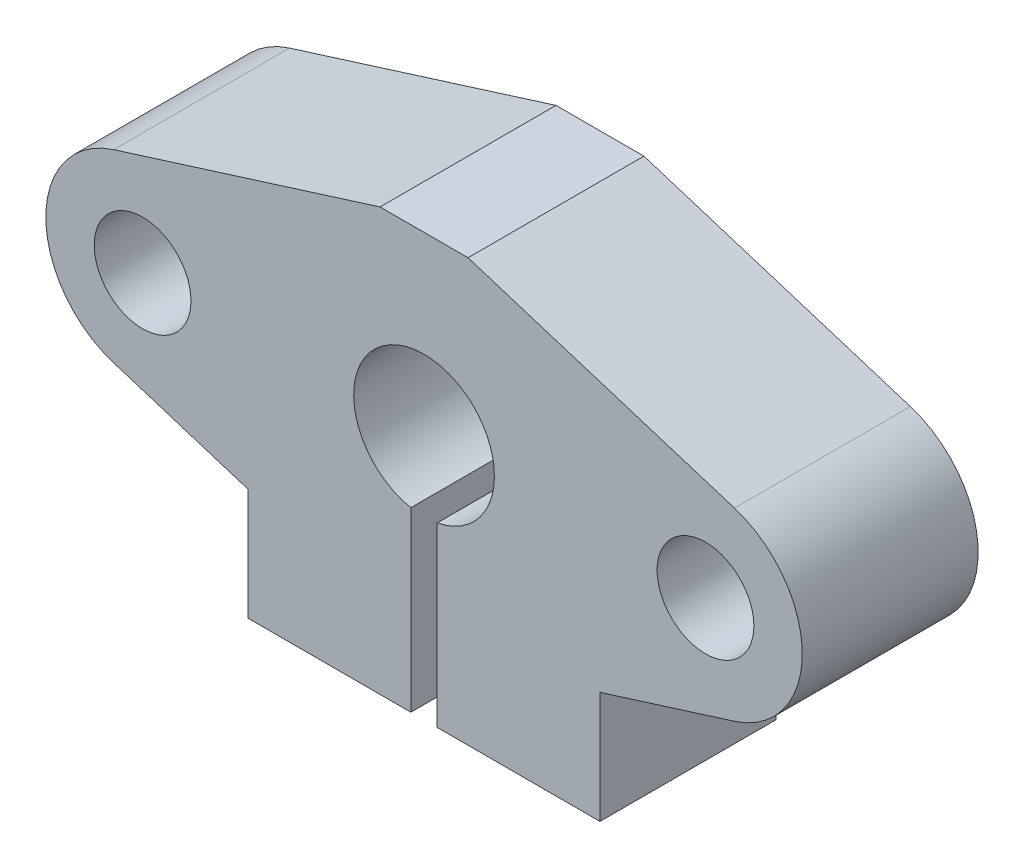
SolidWorks part; units mm, degrees
ref_plane "前视基准面" through (0, 0, 0) normal (0, 0, 1) x (1, 0, 0)
ref_plane "上视基准面" through (0, 0, 0) normal (0, 1, 0) x (1, 0, 0)
ref_plane "右视基准面" through (0, 0, 0) normal (1, 0, 0) x (0, 0, -1)
sketch "草图1" plane through (0, 0, 0) normal (0, 0, 1) x (1, 0, 0)
  line L0 (-17.6465, -5.2478) -> (-2.5, -10)
  line L1 (-2.5, -10) -> (2.5, -10)
  line L2 (2.5, -10) -> (17.6465, -5.2478)
  line L3 (17.6465, 5.2478) -> (2.5, 10)
  line L4 (2.5, 10) -> (-2.5, 10)
  line L5 (-2.5, 10) -> (-17.6465, 5.2478)
  line L6 (-394.8201, 0) -> (19295.64, 0) construction
  line L7 (0, -393.8092) -> (0, 19296.6508) construction
  arc A0 (17.6465, -5.2478) -> (17.6465, 5.2478) centre (16, 0) ccw
  arc A1 (-17.6465, 5.2478) -> (-17.6465, -5.2478) centre (-16, 0) ccw
  dimension "D2" = 43
  dimension "D3" = 5
  dimension "D4" = 5.5
  dimension "D1" = 20
extrude "凸台-拉伸1" add sketch "草图1" along normal blind 10
sketch "草图2" plane through (0, 0, 10) normal (0, 0, 1) x (1, 0, 0)
  line L0 (0, -1000) -> (0, 49000) construction
  line L1 (-10, 0) -> (10, 0)
  line L2 (-10, 0) -> (-10, -14)
  line L3 (-10, -14) -> (10, -14)
  line L4 (10, 0) -> (10, -14)
  dimension "D1" = 20
  dimension "D2" = 14
extrude "凸台-拉伸2" add sketch "草图2" against normal up to surface (10 mm away) up to face at (0, 0, 0)
sketch "草图3" plane through (0, 0, 10) normal (0, 0, 1) x (1, 0, 0)
  line L0 (-1000, 0) -> (49000, 0) construction
  line L1 (0, -1000) -> (0, 49000) construction
  circle A0 centre (0, 0) radius 4
  circle A1 centre (-16, 0) radius 2.75
  circle A2 centre (16, 0) radius 2.75
  dimension "D1" = 8
  dimension "D2" = 5.5
  dimension "D3" = 32
extrude "切除-拉伸1" cut sketch "草图3" against normal up to next
sketch "草图4" plane through (0, 0, 10) normal (0, 0, 1) x (1, 0, 0)
  line L0 (0, -1000) -> (0, 49000) construction
  line L1 (-10, -14) -> (10, -14) construction
  line L2 (-0.75, 0) -> (0.75, 0)
  line L3 (-0.75, 0) -> (-0.75, -14)
  line L4 (-0.75, -14) -> (0.75, -14)
  line L5 (0.75, 0) -> (0.75, -14)
  dimension "D1" = 1.5
extrude "切除-拉伸2" cut sketch "草图4" against normal up to next
